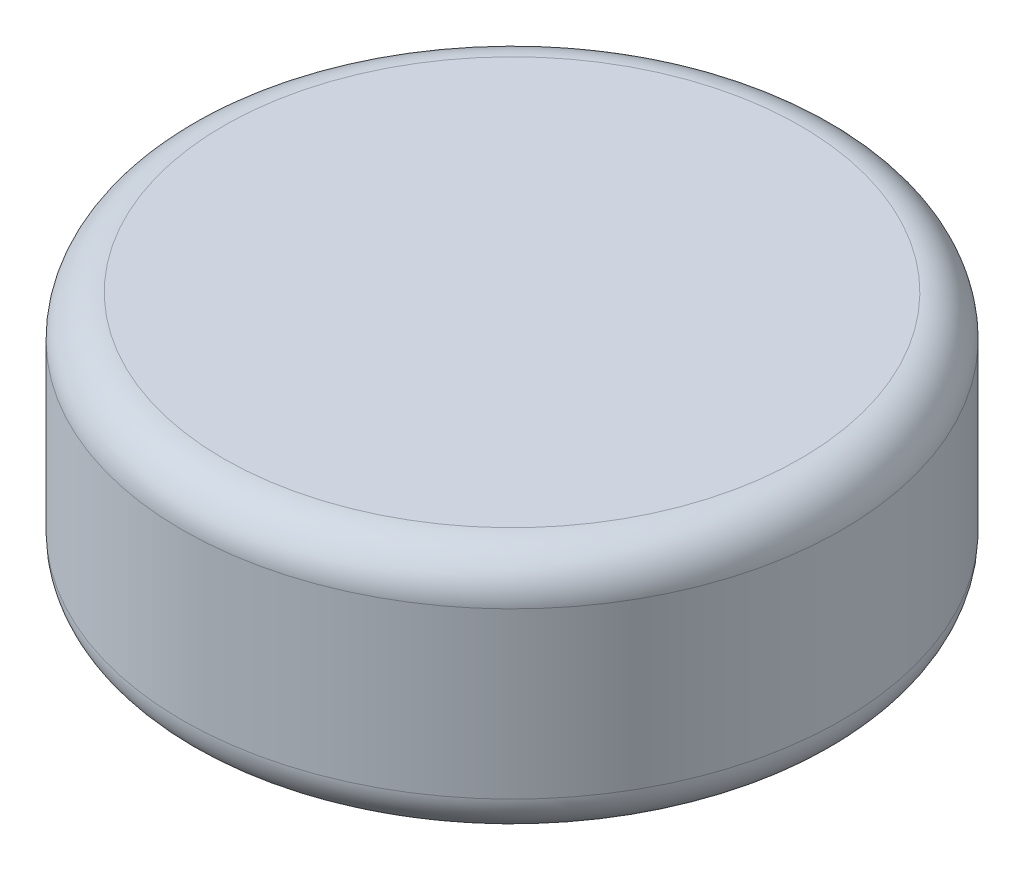
SolidWorks part; units mm, degrees
ref_plane "Front Plane" through (0, 0, 0) normal (0, 0, 1) x (1, 0, 0)
ref_plane "Top Plane" through (0, 0, 0) normal (0, 1, 0) x (1, 0, 0)
ref_plane "Right Plane" through (0, 0, 0) normal (1, 0, 0) x (0, 0, -1)
sketch "Sketch1" plane through (0, 0, 0) normal (0, 1, 0) x (1, 0, 0)
  circle A0 centre (0, 0) radius 4
  dimension "D1" = 8
extrude "Boss-Extrude1" add sketch "Sketch1" along normal blind 3
fillet "Fillet1" radius 0.5 2 edges at (0, 0, 4) (0, 3, 4)
